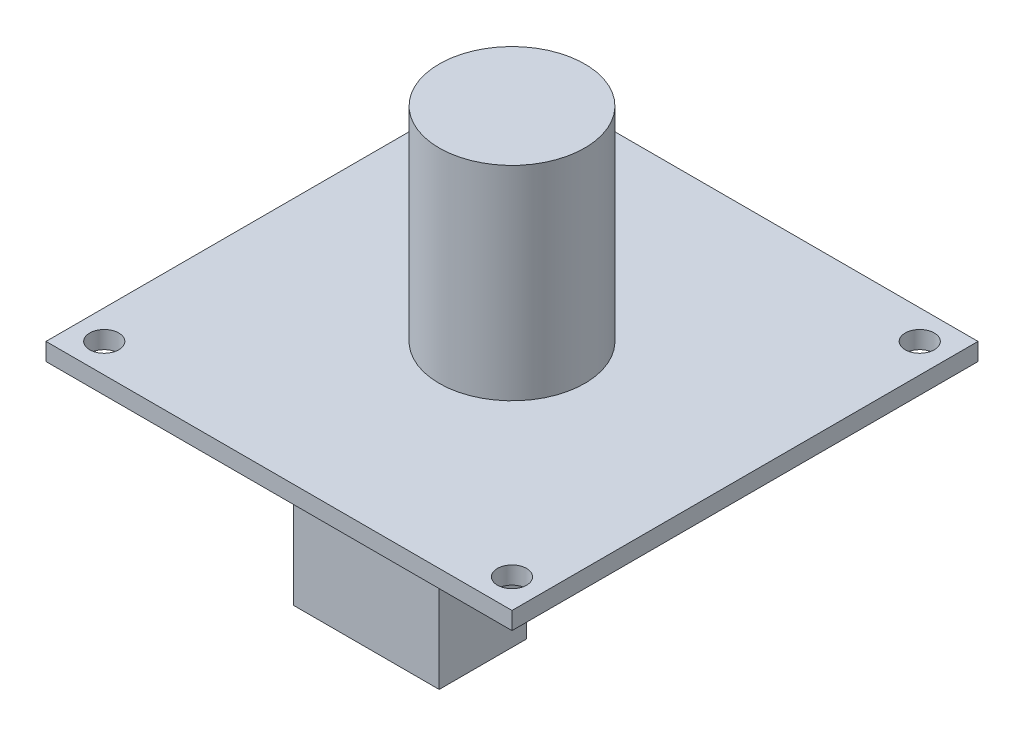
SolidWorks part; units mm, degrees
material "Pure Gold"
ref_plane "Front Plane" through (0, 0, 0) normal (0, 0, 1) x (1, 0, 0)
ref_plane "Top Plane" through (0, 0, 0) normal (0, 1, 0) x (1, 0, 0)
ref_plane "Right Plane" through (0, 0, 0) normal (1, 0, 0) x (0, 0, -1)
sketch "Sketch1" plane through (0, 0, 0) normal (0, 1, 0) x (1, 0, 0)
  line L1 (-16, 16) -> (16, 16)
  line L2 (-16, 16) -> (-16, -16)
  line L3 (-16, -16) -> (16, -16)
  line L4 (16, 16) -> (16, -16)
  line L5 (-16, 16) -> (16, -16) construction
  line L6 (-16, -16) -> (16, 16) construction
  circle A0 centre (-14, 14) radius 1
  circle A1 centre (14, 14) radius 1
  circle A2 centre (14, -14) radius 1
  circle A3 centre (-14, -14) radius 1
  point P0 (0, 0)
  dimension "D3" = 2
  dimension "D1" = 32
  dimension "D4" = 28
extrude "Boss-Extrude1" add sketch "Sketch1" along normal blind 1.2
sketch "Sketch2" plane through (0, 1.2, 0) normal (0, 1, 0) x (1, 0, 0)
  circle A0 centre (0, 0) radius 5
  dimension "D1" = 10
extrude "Boss-Extrude2" add sketch "Sketch2" along normal blind 14
sketch "Sketch3" plane through (0, 0, 0) normal (0, -1, 0) x (1, 0, 0)
  line L0 (-16, -16) -> (-16, 16) construction
  line L1 (-1, 14) -> (9, 14)
  line L2 (-1, 14) -> (-1, 8)
  line L3 (-1, 8) -> (9, 8)
  line L4 (9, 14) -> (9, 8)
  line L5 (-1, 14) -> (9, 8) construction
  line L6 (-1, 8) -> (9, 14) construction
  line L7 (16, 16) -> (16, -16) construction
  line L8 (-16, 16) -> (16, 16) construction
  point P0 (4, 11)
  dimension "D1" = 15
  dimension "D2" = 7
  dimension "D3" = 2
  dimension "D4" = 8
extrude "Boss-Extrude3" add sketch "Sketch3" along normal blind 8
